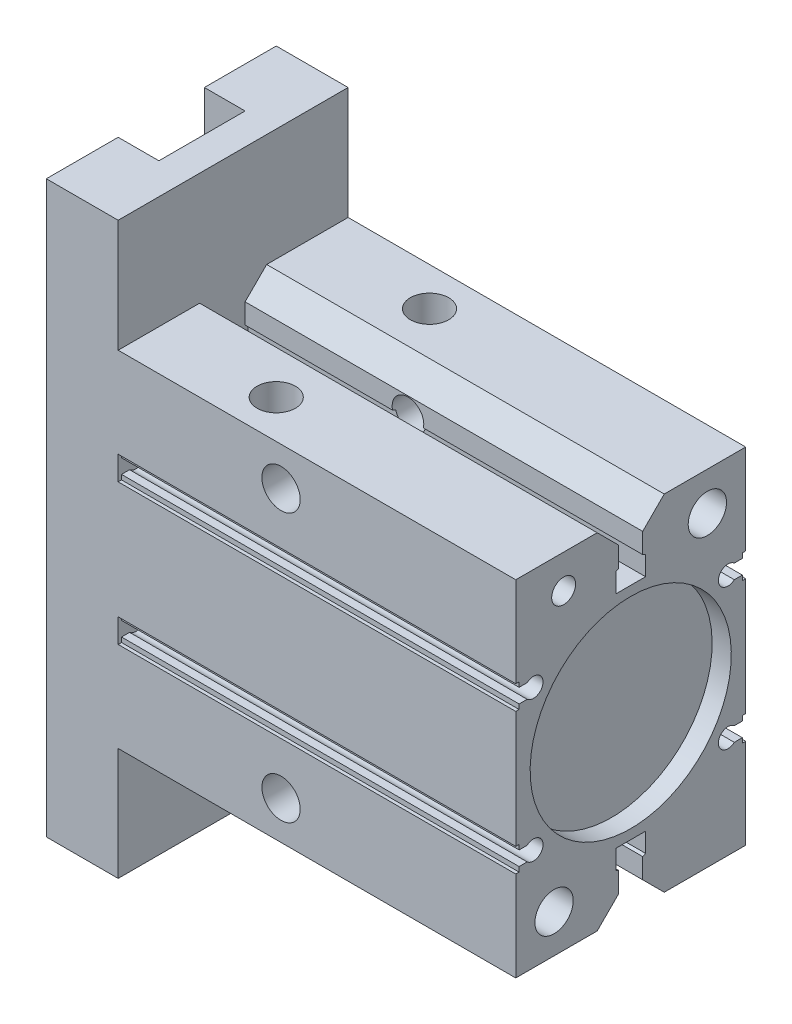
SolidWorks part; units mm, degrees
ref_plane "fwd" through (0, 0, 0) normal (0, 0, 1) x (1, 0, 0)
ref_plane "up" through (0, 0, 0) normal (0, 1, 0) x (1, 0, 0)
ref_plane "rt" through (0, 0, 0) normal (1, 0, 0) x (0, 0, -1)
sketch "sk-main" plane through (0, 0, 0) normal (0, 0, 1) x (1, 0, 0)
  line L0 (0, -36) -> (83, -36)
  line L1 (83, -36) -> (83, 36)
  line L2 (83, 36) -> (0, 36)
  line L3 (0, 36) -> (0, 59.5)
  line L4 (0, 59.5) -> (-15, 59.5)
  line L5 (-15, 59.5) -> (-15, -59.5)
  line L6 (-15, -59.5) -> (0, -59.5)
  line L7 (0, -59.5) -> (0, -36)
  line L8 (-10.15, 0) -> (48.15, 0) construction
  line L9 (0, -13.9186) -> (0, 13.9186) construction
  line L10 (14.2498, 0) -> (-14.2498, 0) construction
  dimension "D1" = 83
  dimension "j" = 72
  dimension "o" = 119
  dimension "D131" = 15
extrude "main" add sketch "sk-main" along normal mid plane 48
sketch "sk-recess" plane through (83, 0, 0) normal (1, 0, 0) x (0, 0, -1)
  circle A0 centre (0, 0) radius 21
  dimension "D30" = 42
extrude "recess" cut sketch "sk-recess" against normal blind 4
sketch "sk-NUT" plane through (83, 0, 0) normal (1, 0, 0) x (0, 0, -1)
  line L0 (-21.6229, 16.2) -> (-24, 16.2)
  line L1 (-21.6229, 13.2) -> (-24, 13.2)
  line L2 (-24, 16.2) -> (-24, 13.2)
  line L3 (-21.6229, -13.2) -> (-24, -13.2)
  line L4 (-24, -16.2) -> (-24, -13.2)
  line L5 (-21.6229, -16.2) -> (-24, -16.2)
  line L6 (21.6229, 13.2) -> (24, 13.2)
  line L7 (21.6229, 16.2) -> (24, 16.2)
  line L8 (24, 16.2) -> (24, 13.2)
  line L9 (21.6229, -13.2) -> (24, -13.2)
  line L10 (24, -16.2) -> (24, -13.2)
  line L11 (21.6229, -16.2) -> (24, -16.2)
  line L13 (-12.98, 14.7) -> (12.98, 14.7) construction
  line L14 (-12.98, 0) -> (12.98, 0) construction
  line L15 (0, -8.58) -> (0, 8.58) construction
  line L16 (14.2498, 0) -> (-14.2498, 0) construction
  line L17 (0, 21.9767) -> (0, -21.9767) construction
  line L18 (-24, -36) -> (-24, 36) construction
  line L19 (24, -36) -> (24, 36) construction
  arc A0 (-21.6229, 13.2) -> (-21.6229, 16.2) centre (-20.3, 14.7) ccw
  arc A1 (-21.6229, -16.2) -> (-21.6229, -13.2) centre (-20.3, -14.7) ccw
  arc A2 (21.6229, 16.2) -> (21.6229, 13.2) centre (20.3, 14.7) ccw
  arc A3 (21.6229, -13.2) -> (21.6229, -16.2) centre (20.3, -14.7) ccw
  dimension "D61" = 4
  dimension "D110" = 29.4
  dimension "D2" = 3
  dimension "D60" = 3.7
extrude "NUT" cut sketch "sk-NUT" against normal up to surface (83 mm away) up to face at (0, 47.75, 0)
sketch "sk-hole1" plane through (83, 0, 0) normal (1, 0, 0) x (0, 0, -1)
  line L0 (0, 21.9767) -> (0, -21.9767) construction
  line L1 (14.2498, 0) -> (-14.2498, 0) construction
  circle A0 centre (-14, 29) radius 2.5
  dimension "D109" = 5
  dimension "D106" = 14
  dimension "D107" = 29
extrude "hole1" cut sketch "sk-hole1" against normal blind 5
sketch "sk-hole_t" plane through (83, 0, 0) normal (1, 0, 0) x (0, 0, -1)
  line L0 (-16, -28) -> (16, 28) construction
  circle A0 centre (-16, -28) radius 4
  circle A1 centre (16, 28) radius 4
  dimension "t" = 8
  dimension "p" = 32
  dimension "s" = 56
extrude "hole_t" cut sketch "sk-hole_t" against normal blind 17
sketch "sk-hole2" plane through (0, 36, 0) normal (0, 1, 0) x (-1, 0, 0)
  line L0 (-20, 0) -> (17.7, 0) construction
  line L1 (21.9767, 0) -> (-21.9767, 0) construction
  line L2 (-83, 24) -> (-83, -24) construction
  circle A0 centre (-25, -16) radius 4
  circle A1 centre (-25, 16) radius 4
  dimension "D118" = 8
  dimension "D117" = 32
  dimension "D119" = 58
extrude "hole2" cut sketch "sk-hole2" against normal blind 13
sketch "sk-hole3" plane through (0, 0, -24) normal (0, 0, -1) x (-1, 0, 0)
  line L0 (-50, 0) -> (10, 0) construction
  line L1 (-83, -36) -> (-83, -16.2) construction
  line L2 (14.2498, 0) -> (-14.2498, 0) construction
  circle A0 centre (-34, 28) radius 4
  circle A1 centre (-34, -28) radius 4
  dimension "D122" = 8
  dimension "D121" = 56
  dimension "D123" = 49
extrude "hole3" cut sketch "sk-hole3" against normal blind 16
mirror "Mirror1" about plane through (0, 0, 0) normal (0, 0, 1) of "hole3"
sketch "Sketch1" plane through (0, 0, 24) normal (0, 0, 1) x (1, 0, 0)
  line L0 (0, 0) -> (70, 0) construction
  circle A0 centre (34, 28) radius 3.3
  circle A1 centre (34, -28) radius 3.3
  circle A2 centre (34, -28) radius 4 construction
  dimension "D1" = 6.6
extrude "ThruHoles" cut sketch "Sketch1" against normal through all
sketch "sk-prong_grv" plane through (0, 0, 0) normal (0, 0, 1) x (1, 0, 0)
  line L0 (-15, 59.5) -> (-6.5, 59.5)
  line L1 (-6.5, 59.5) -> (-6.5, -59.5)
  line L3 (-15, -59.5) -> (-15, 59.5)
  line L6 (-6.5, -59.5) -> (-15, -59.5)
  line L8 (-7.75, 0) -> (-2.25, 0) construction
  line L9 (14.2498, 0) -> (-14.2498, 0) construction
  line L12 (-15, 59.5) -> (-15, -59.5) construction
  line L13 (0, 59.5) -> (-15, 59.5) construction
  dimension "D133" = 8.5
extrude "prong_grv" cut sketch "sk-prong_grv" against normal mid plane 18
sketch "sk-hole4" plane through (0, -36, 0) normal (0, -1, 0) x (1, 0, 0)
  line L0 (71, -14) -> (45, 14) construction
  line L3 (21.9767, 0) -> (-21.9767, 0) construction
  line L4 (83, 24) -> (83, -24) construction
  line L5 (83, 24) -> (83, -24) construction
  circle A0 centre (45, 14) radius 2.5
  circle A1 centre (71, -14) radius 2.5
  point P4 (58, 0)
  dimension "D152" = 5
  dimension "D155" = 38
  dimension "D154" = 12
  dimension "D151" = 28
extrude "hole4" cut sketch "sk-hole4" against normal blind 5
sketch "Sketch3" [suppressed] plane through (30, 0, 0) normal (1, 0, 0) x (0, 0, -1)
  line L0 (0, 0) -> (0, 6) construction
  line L1 (5, 6) -> (-5, 6) construction
  line L2 (0, 0) -> (-0.8, 0) construction
  line L3 (-0.8, -5) -> (-0.8, -10) construction
  line L4 (0, 0) -> (0.8, 0) construction
  line L5 (-4.8, -3) -> (-4.8, 3)
  line L6 (4.8, -3) -> (4.8, 3)
  line L7 (-4.8, 3) -> (-5, 3)
  line L8 (-5, -10) -> (-5, 10) construction
  line L9 (4.8, 3) -> (5, 3)
  line L10 (-4.8, -3) -> (-5, -3)
  line L11 (4.8, -3) -> (5, -3)
  line L12 (-5, -3) -> (-5, 3)
  line L13 (5, -10) -> (5, 10) construction
  line L14 (5, -3) -> (5, 3)
  dimension "D1" = 0.2
  dimension "D2" = 6
extrude "Cut-Extrude1" [suppressed] cut sketch "Sketch3" against normal up to surface (30 mm away)
sketch "Sketch4" plane through (83, 0, 0) normal (1, 0, 0) x (0, 0, -1)
  line L0 (0, 0) -> (0, 15.4434) construction
  line L1 (-24, 36) -> (24, 36) construction
  line L2 (-3.7229, 36) -> (-1.0771, 36)
  line L3 (-1.0771, 36) -> (-1.0771, 35)
  line L4 (-3.7229, 36) -> (-3.7229, 35)
  line L5 (3.7229, 36) -> (3.7229, 35)
  line L6 (1.0771, 36) -> (1.0771, 35)
  line L7 (3.7229, 36) -> (1.0771, 36)
  arc A0 (-3.7229, 35) -> (-1.0771, 35) centre (-2.4, 33.5) ccw
  arc A1 (3.7229, 35) -> (1.0771, 35) centre (2.4, 33.5) cw
  dimension "D1" = 4
  dimension "D2" = 4.8
  dimension "D3" = 2.5
  dimension "D4" = 1
extrude "6BoreSwitchGroove" [suppressed] cut sketch "Sketch4" against normal blind 21
sketch "sk-grv" plane through (83, 0, 0) normal (1, 0, 0) x (0, 0, -1)
  line L0 (-2.5, 36) -> (-2.5, 27.3)
  line L1 (-2.5, 27.3) -> (-3.1, 27.0202)
  line L2 (-3.1, 27.0202) -> (-3.1, 23)
  line L3 (-3.1, 23) -> (3.1, 23)
  line L4 (3.1, 23) -> (3.1, 27.0202)
  line L5 (3.1, 27.0202) -> (2.5, 27.3)
  line L6 (2.5, 27.3) -> (2.5, 36)
  line L7 (-2.5, 36) -> (2.5, 36)
  line L8 (3.1, -23) -> (3.1, -27.0202)
  line L9 (3.1, -27.0202) -> (2.5, -27.3)
  line L10 (2.5, -27.3) -> (2.5, -36)
  line L11 (-2.5, -36) -> (2.5, -36)
  line L12 (-2.5, -36) -> (-2.5, -27.3)
  line L13 (-2.5, -27.3) -> (-3.1, -27.0202)
  line L14 (-3.1, -27.0202) -> (-3.1, -23)
  line L15 (-3.1, -23) -> (3.1, -23)
  line L16 (0, -16.83) -> (0, 16.83) construction
  line L17 (-3.41, 0) -> (3.41, 0) construction
  line L18 (0, 21.9767) -> (0, -21.9767) construction
  line L19 (14.2498, 0) -> (-14.2498, 0) construction
  line L20 (-24, 36) -> (24, 36) construction
  line L21 (-24, -36) -> (24, -36) construction
  dimension "D19" = 5
  dimension "D20" = 13
  dimension "d21" = 115
  dimension "D22" = 6.2
  dimension "D23" = 8.7
extrude "grv" cut sketch "sk-grv" against normal up to surface (83 mm away) up to face at (0, 47.75, 0)
chamfer "32-40SwitchChamfer" distance 4.5 angle 45 4 edges at (41.5, -36, 2.5) (41.5, -36, -2.5) (41.5, 36, -2.5) (41.5, 36, 2.5)
sketch "Sketch5" plane through (0, 0, 0) normal (1, 0, 0) x (0, 0, -1)
  line L0 (-24, 16.2) -> (-24, 36) construction
  line L1 (-24, 17.2) -> (-23.3, 17.2)
  line L2 (-24, 17.2) -> (-24, 12.2)
  line L3 (-24, 12.2) -> (-23.3, 12.2)
  line L4 (-23.3, 17.2) -> (-23.3, 12.2)
  line L5 (0, 0) -> (0, 58.8903) construction
  line L6 (0, 0) -> (33.5078, 0) construction
  line L7 (23.3, 17.2) -> (23.3, 12.2)
  line L8 (24, 12.2) -> (23.3, 12.2)
  line L9 (24, 17.2) -> (24, 12.2)
  line L10 (24, 17.2) -> (23.3, 17.2)
  line L11 (24, -17.2) -> (23.3, -17.2)
  line L12 (24, -17.2) -> (24, -12.2)
  line L13 (24, -12.2) -> (23.3, -12.2)
  line L14 (23.3, -17.2) -> (23.3, -12.2)
  line L15 (-23.3, -17.2) -> (-23.3, -12.2)
  line L16 (-24, -12.2) -> (-23.3, -12.2)
  line L17 (-24, -17.2) -> (-24, -12.2)
  line L18 (-24, -17.2) -> (-23.3, -17.2)
  arc A0 (-21.6229, 13.2) -> (-21.6229, 16.2) centre (-20.3, 14.7) ccw construction
  arc A1 (-21.6229, 13.2) -> (-21.6229, 16.2) centre (-20.3, 14.7) ccw construction
  point P9 (-23.3, 14.7)
  dimension "D1" = 5
  dimension "D2" = 0.7
extrude "32-40SwitchCutDetail" cut sketch "Sketch5" along normal through all
sketch "Sketch6" plane through (0, -31, 0) normal (0, -1, 0) x (1, 0, 0)
  circle A0 centre (71, -14) radius 2.5
  circle A1 centre (71, -14) radius 2.5 construction
extrude "Extrude1" add sketch "Sketch6" along normal up to surface (5 mm away) up to face at (47.5, -36, 14)
sketch "Sketch8" plane through (0, 36, 0) normal (0, 1, 0) x (1, 0, 0)
  line L0 (83, -24) -> (0, -24) construction
  line L1 (83, -24) -> (83, -7) construction
  circle A0 centre (63.7, -21.3) radius 4
  circle A1 centre (25, 16) radius 4 construction
  dimension "D2" = 19.3
  dimension "D1" = 2.7
extrude "Cut-Extrude3" [suppressed] cut sketch "Sketch8" against normal blind 6
sketch "Sketch9" plane through (0, -36, 0) normal (0, -1, 0) x (1, 0, 0)
  line L0 (83, 24) -> (83, 7) construction
  circle A0 centre (71, -14) radius 2.5
  circle A1 centre (45, 14) radius 2.5 construction
  circle A2 centre (45, 14) radius 2.5 construction
  dimension "D1" = 28
  dimension "D2" = 12
extrude "Hole 5" cut sketch "Sketch9" against normal up to surface (5 mm away) up to face at (47.5, -31, 14)
